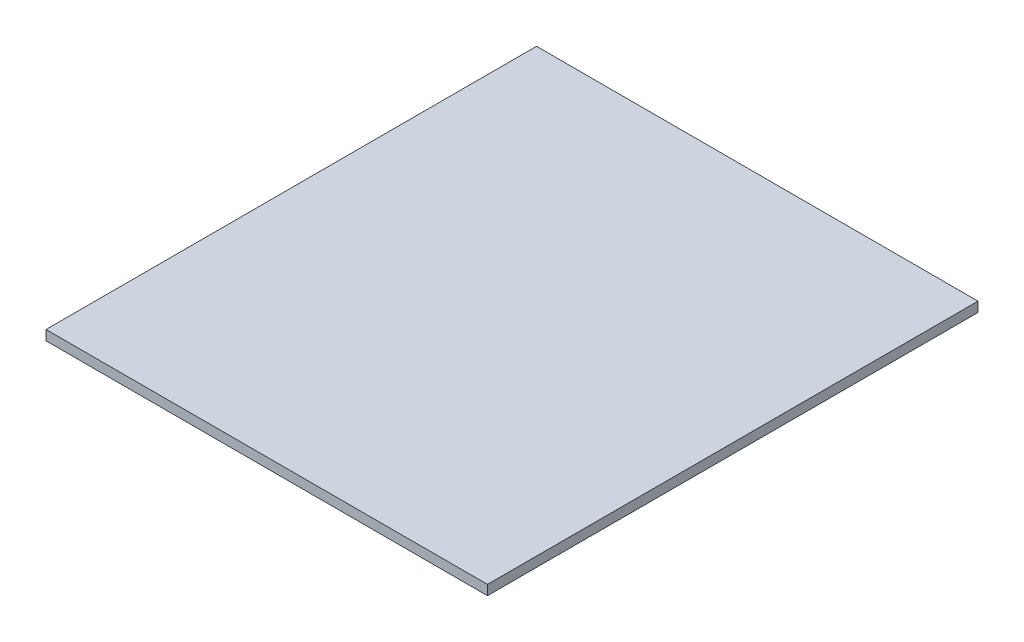
SolidWorks part; units mm, degrees
ref_plane "Front Plane" through (0, 0, 0) normal (0, 0, 1) x (1, 0, 0)
ref_plane "Top Plane" through (0, 0, 0) normal (0, 1, 0) x (1, 0, 0)
ref_plane "Right Plane" through (0, 0, 0) normal (1, 0, 0) x (0, 0, -1)
sketch "Sketch1" plane through (0, 0, 0) normal (0, 1, 0) x (1, 0, 0)
  line L1 (0, 0) -> (22.86, 0)
  line L2 (0, 0) -> (0, 25.4)
  line L3 (0, 25.4) -> (22.86, 25.4)
  line L4 (22.86, 0) -> (22.86, 25.4)
  dimension "D1" = 25.4
  dimension "D2" = 22.86
extrude "Boss-Extrude1" add sketch "Sketch1" along normal blind 0.508
